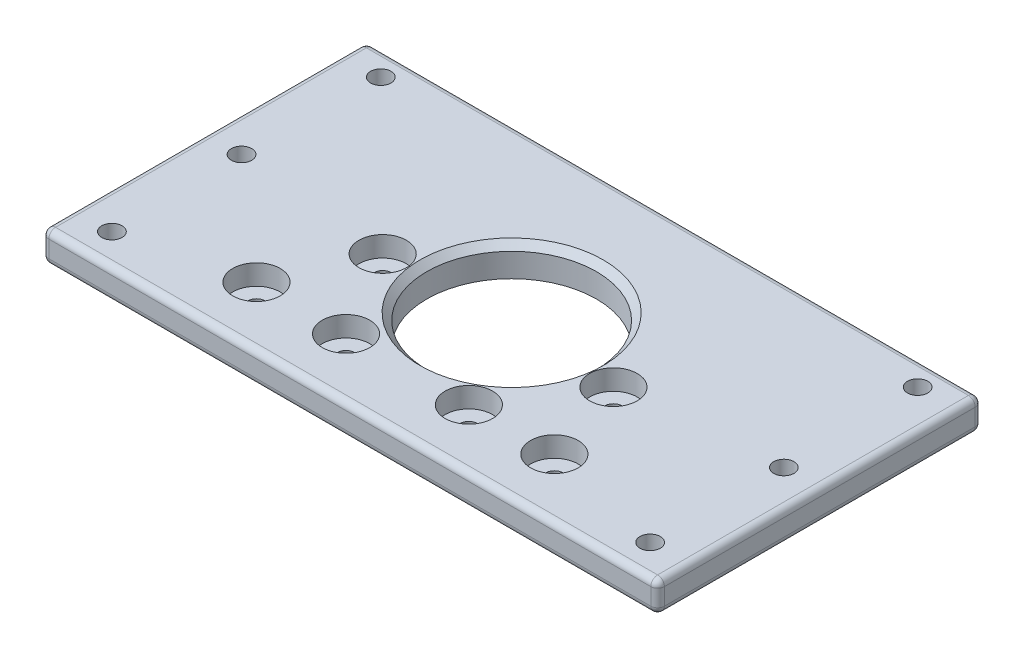
SolidWorks part; units mm, degrees
ref_plane "Front Plane" through (0, 0, 0) normal (0, 0, 1) x (1, 0, 0)
ref_plane "Top Plane" through (0, 0, 0) normal (0, 1, 0) x (1, 0, 0)
ref_plane "Right Plane" through (0, 0, 0) normal (1, 0, 0) x (0, 0, -1)
sketch "Sketch1" plane through (0, 0, 0) normal (0, 1, 0) x (1, 0, 0)
  line L1 (0, 0) -> (90.71, 0)
  line L2 (0, 0) -> (0, 47.8)
  line L3 (0, 47.8) -> (90.71, 47.8)
  line L4 (90.71, 0) -> (90.71, 47.8)
  circle A0 centre (85.01, 4.6) radius 1.5
  circle A1 centre (85.31, 24) radius 1.5
  circle A2 centre (84.91, 44.12) radius 1.5
  circle A3 centre (5.8, 44.12) radius 1.5
  circle A4 centre (5.4, 24) radius 1.5
  circle A5 centre (5.7, 4.6) radius 1.5
  circle A6 centre (28.5, 21.7) radius 1.25
  circle A7 centre (22.8, 8.8) radius 1.25
  circle A8 centre (36, 8.8) radius 1.25
  circle A9 centre (54.1, 8.8) radius 1.25
  circle A10 centre (66.7, 8.8) radius 1.25
  circle A11 centre (62.5, 21.7) radius 1.25
  circle A12 centre (45.5, 23.7) radius 12.5
  point P31 (46.535, 28.5466)
  point P32 (0, 0)
  point P33 (0, 0)
  point P34 (0, 0)
  point P35 (28.5, 21.7775)
  dimension "D12" = 3
  dimension "D14" = 22.7
  dimension "D15" = 25
  dimension "D16" = 2.5
  dimension "D18" = 13.2
  dimension "D19" = 18.1
  dimension "D20" = 12.6
  dimension "D1" = 90.71
  dimension "D2" = 47.8
  dimension "D3" = 5.7
  dimension "D4" = 4.6
  dimension "D5" = 5.7
  dimension "D6" = 5.4
  dimension "D7" = 19.4
  dimension "D8" = 5.4
  dimension "D9" = 5.8
  dimension "D10" = 5.8
  dimension "D11" = 3.68
  dimension "D13" = 8.8
  dimension "D17" = 23.7
  dimension "D21" = 45.5
  dimension "D22" = 17
  dimension "D23" = 17
  dimension "D24" = 2
extrude "Boss-Extrude1" add sketch "Sketch1" along normal blind 4.5
sketch "Sketch2" plane through (0, 4.5, 0) normal (0, 1, 0) x (1, 0, 0)
  circle A0 centre (28.5, 21.7) radius 3.5
  circle A1 centre (22.8, 8.8) radius 3.5
  circle A2 centre (36, 8.8) radius 3.5
  circle A3 centre (54.1, 8.8) radius 3.5
  circle A4 centre (66.7, 8.8) radius 3.5
  circle A5 centre (62.5, 21.7) radius 3.5
  dimension "D1" = 7
extrude "Cut-Extrude1" cut sketch "Sketch2" against normal blind 3
chamfer "Chamfer1" distance 1 angle 45 1 edges at (45.5, 4.5, -11.2)
fillet "Fillet1" radius 1 12 edges at (45.355, 0, 0) (90.71, 0, -23.9) (45.355, 0, -47.8) (0, 0, -23.9) (90.71, 2.25, -47.8) (90.71, 2.25, 0) (0, 2.25, 0) (0, 2.25, -47.8) (90.71, 4.5, -23.9) (45.355, 4.5, 0) (45.355, 4.5, -47.8) (0, 4.5, -23.9)
